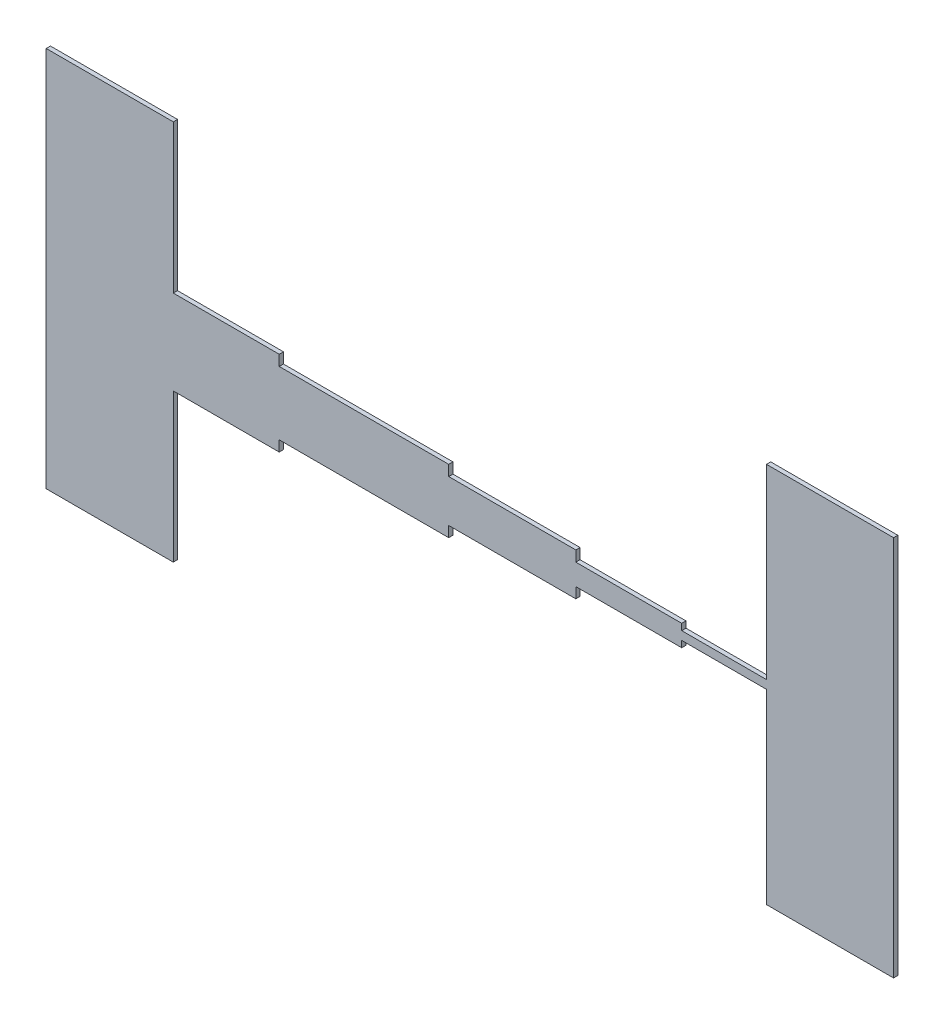
SolidWorks part; units mm, degrees
ref_plane "Front Plane" through (0, 0, 0) normal (0, 0, 1) x (1, 0, 0)
ref_plane "Top Plane" through (0, 0, 0) normal (0, 1, 0) x (1, 0, 0)
ref_plane "Right Plane" through (0, 0, 0) normal (1, 0, 0) x (0, 0, -1)
sketch "Sketch2" plane through (0, 0, 0) normal (0, 0, 1) x (1, 0, 0)
  line L0 (3, 9) -> (3, 0) construction
  line L1 (0, 0) -> (3, 0)
  line L2 (0, 0) -> (0, 9)
  line L3 (0, 9) -> (3, 9)
  line L4 (20, 0) -> (20, 9)
  line L5 (17, 9) -> (17, 0) construction
  line L6 (3, 4.5) -> (17, 4.5) construction
  line L7 (3, 9) -> (3, 5.5)
  line L8 (3, 5.5) -> (5.5, 5.5)
  line L10 (3, 3.5) -> (5.5, 3.5)
  line L11 (5.5, 5.5) -> (5.5, 5.25)
  line L12 (0.5, 5.5) -> (5.5, 3.5) construction
  line L13 (0.5, 3.5) -> (5.5, 5.5) construction
  line L14 (17, 9) -> (17, 4.6)
  line L15 (5.5, 5.25) -> (9.5, 5.25)
  line L16 (1.5, 5.25) -> (1.5, 5.1)
  line L17 (5.5, 3.75) -> (9.5, 3.75)
  line L18 (9.5, 5.25) -> (9.5, 5)
  line L19 (1.5, 5.25) -> (9.5, 3.75) construction
  line L20 (1.5, 3.75) -> (9.5, 5.25) construction
  line L21 (9.5, 5) -> (12.5, 5)
  line L23 (9.5, 4) -> (12.5, 4)
  line L24 (12.5, 5) -> (12.5, 4.75)
  line L25 (6.5, 5) -> (12.5, 4) construction
  line L26 (6.5, 4) -> (12.5, 5) construction
  line L27 (12.5, 4.75) -> (15, 4.75)
  line L29 (12.5, 4.25) -> (15, 4.25)
  line L30 (15, 4.75) -> (15, 4.6)
  line L31 (10, 4.75) -> (15, 4.25) construction
  line L32 (10, 4.25) -> (15, 4.75) construction
  line L33 (15, 4.4) -> (17, 4.4)
  line L35 (15, 4.6) -> (17, 4.6)
  line L37 (13, 4.4) -> (17, 4.6) construction
  line L38 (13, 4.6) -> (17, 4.4) construction
  line L39 (1.5, 3.9) -> (1.5, 3.75)
  line L40 (17, 0) -> (20, 0)
  line L41 (17, 9) -> (20, 9)
  line L42 (3, 3.5) -> (3, 0)
  line L43 (5.5, 3.75) -> (5.5, 3.5)
  line L44 (9.5, 4) -> (9.5, 3.75)
  line L45 (12.5, 4.25) -> (12.5, 4)
  line L46 (15, 4.4) -> (15, 4.25)
  line L47 (17, 4.4) -> (17, 0)
  point P15 (5.5, 4.5)
  point P20 (9.5, 4.5)
  point P25 (12.5, 4.5)
  point P30 (15, 4.5)
  dimension "D1" = 20
  dimension "D2" = 9
  dimension "D3" = 3
  dimension "D4" = 3
  dimension "D5" = 5
  dimension "D6" = 2
  dimension "D7" = 4
  dimension "D8" = 1.5
  dimension "D9" = 3
  dimension "D10" = 1
  dimension "D11" = 2.5
  dimension "D12" = 0.5
  dimension "D13" = 0.2
extrude "Boss-Extrude1" add sketch "Sketch2" against normal blind 0.1 contours L3 L7 L8 L11 L15 L18 L21 L24 L27 L30 L35 L14 L41 L4 L40 L47 L33 L46 L29 L45 L23 L44 L17 L43 L10 L42 L1 L2
scale "Scale1" bodies to scale 101 scale about centroid uniform scaling yes scale factor 1000
